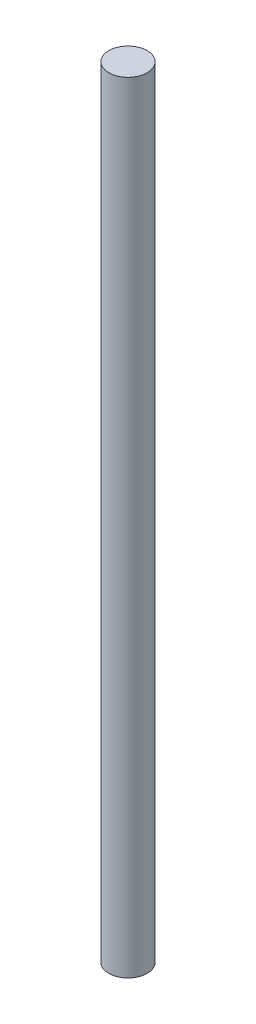
SolidWorks part; units mm, degrees
ref_plane "Front Plane" through (0, 0, 0) normal (0, 0, 1) x (1, 0, 0)
ref_plane "Top Plane" through (0, 0, 0) normal (0, 1, 0) x (1, 0, 0)
ref_plane "Right Plane" through (0, 0, 0) normal (1, 0, 0) x (0, 0, -1)
sketch "Sketch1" plane through (0, 0, 0) normal (0, 1, 0) x (1, 0, 0)
  circle A0 centre (0, 0) radius 2.5
  dimension "D1" = 5
extrude "Boss-Extrude1" add sketch "Sketch1" along normal blind 101.6
cosmetic thread "Cosmetic Thread5" parameters "D1"=101.6, "D2"=3.5662
